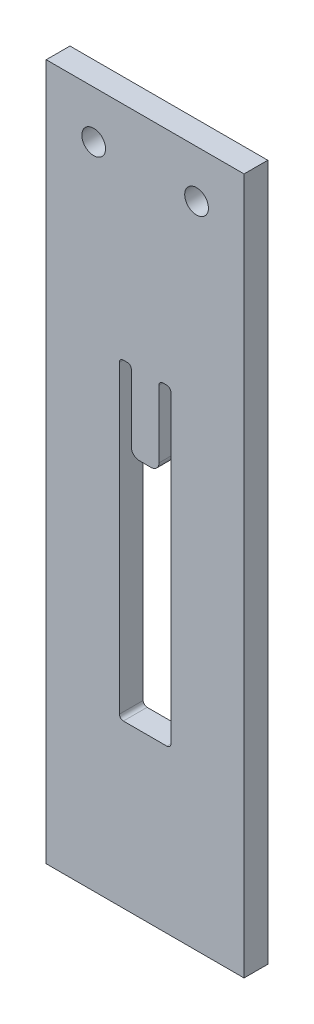
SolidWorks part; units mm, degrees
ref_plane "Front Plane" through (0, 0, 0) normal (0, 0, 1) x (1, 0, 0)
ref_plane "Top Plane" through (0, 0, 0) normal (0, 1, 0) x (1, 0, 0)
ref_plane "Right Plane" through (0, 0, 0) normal (1, 0, 0) x (0, 0, -1)
sketch "Sketch1" plane through (0, 0, 0) normal (0, 0, 1) x (1, 0, 0)
  line L1 (0, 0) -> (25, 0)
  line L2 (0, 0) -> (0, 88)
  line L3 (0, 88) -> (25, 88)
  line L4 (25, 0) -> (25, 88)
  dimension "D1" = 25
  dimension "D2" = 88
extrude "Boss-Extrude1" add sketch "Sketch1" along normal blind 3
sketch "Sketch2" plane through (0, 0, 3) normal (0, 0, 1) x (1, 0, 0)
  line L0 (25, 0) -> (25, 88) construction
  line L1 (25, 88) -> (0, 88) construction
  line L2 (0, 88) -> (0, 0) construction
  circle A0 centre (19, 82) radius 1.5
  circle A1 centre (6, 82) radius 1.5
  point P10 (0, 0)
  dimension "D1" = 6
  dimension "D2" = 3
  dimension "D3" = 6
  dimension "D4" = 6
extrude "Cut-Extrude1" cut sketch "Sketch2" against normal blind 3
sketch "Sketch3" plane through (0, 0, 3) normal (0, 0, 1) x (1, 0, 0)
  line L1 (9.75, 20.5) -> (15.25, 20.5)
  line L2 (9.25, 21) -> (9.25, 59.5)
  line L3 (9.75, 60) -> (10.25, 60)
  line L4 (15.75, 21) -> (15.75, 59.5)
  line L5 (14.1, 0) -> (14.1, 80) construction
  line L6 (0, 0) -> (25, 0) construction
  line L7 (14.75, 60) -> (15.25, 60)
  line L8 (15.75, 40.25) -> (37.9796, 40.25) construction
  line L10 (9.25, 21) -> (0, 21) construction
  line L11 (0, 88) -> (0, 0) construction
  line L12 (15.75, 21) -> (25, 21) construction
  line L13 (25, 0) -> (25, 88) construction
  line L16 (10.75, 59.5) -> (10.75, 51)
  line L17 (11.75, 50) -> (13.25, 50)
  line L18 (14.25, 59.5) -> (14.25, 51)
  arc A0 (15.75, 21) -> (15.25, 20.5) centre (15.25, 21) cw
  arc A1 (9.25, 21) -> (9.75, 20.5) centre (9.75, 21) ccw
  arc A2 (15.25, 60) -> (15.75, 59.5) centre (15.25, 59.5) cw
  arc A3 (14.75, 60) -> (14.25, 59.5) centre (14.75, 59.5) ccw
  arc A4 (10.25, 60) -> (10.75, 59.5) centre (10.25, 59.5) cw
  arc A5 (9.25, 59.5) -> (9.75, 60) centre (9.75, 59.5) cw
  arc A6 (13.25, 50) -> (14.25, 51) centre (13.25, 51) ccw
  arc A7 (10.75, 51) -> (11.75, 50) centre (11.75, 51) ccw
  point P4 (14.1, 20.5)
  point P10 (12.5, 0)
  point P17 (14.1, 60)
  point P20 (14.25, 60)
  point P29 (14.25, 50)
  point P33 (10.75, 50)
  dimension "D2" = 20.5
  dimension "D6" = 1
  dimension "D5" = 0.5
  dimension "D3" = 39.5
  dimension "D4" = 6.5
  dimension "D8" = 10
  dimension "D9" = 1.5
  dimension "D10" = 3.5
extrude "Cut-Extrude2" cut sketch "Sketch3" against normal blind 10
